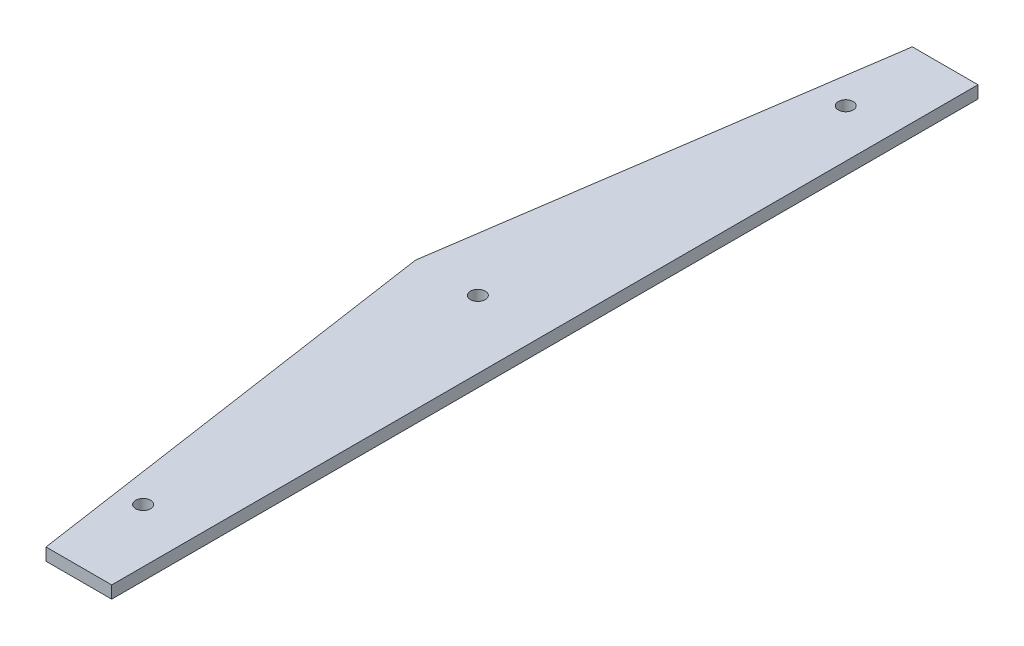
SolidWorks part; units mm, degrees
ref_plane "Front Plane" through (0, 0, 0) normal (0, 0, 1) x (1, 0, 0)
ref_plane "Top Plane" through (0, 0, 0) normal (0, 1, 0) x (1, 0, 0)
ref_plane "Right Plane" through (0, 0, 0) normal (1, 0, 0) x (0, 0, -1)
sketch "Sketch1" plane through (0, 7.6595, 0) normal (0, 1, 0) x (1, 0, 0)
  line L1 (-141.5163, 104.251) -> (-124.6714, 104.251)
  line L3 (-141.5163, -117.7997) -> (-124.6714, -117.7997)
  line L4 (-124.6714, 104.251) -> (-124.6714, -117.7997)
  line L8 (-141.5163, 104.251) -> (-157.8295, -6.7743)
  line L9 (-157.8295, -6.7743) -> (-141.5163, -117.7997)
  circle A0 centre (-136.9565, 82.6365) radius 1.8987
  circle A1 centre (-142.0163, -6.6086) radius 1.8987
  circle A2 centre (-138.4932, -95.9277) radius 1.8987
extrude "MainBody" add sketch "Sketch1" against normal blind 3.175
